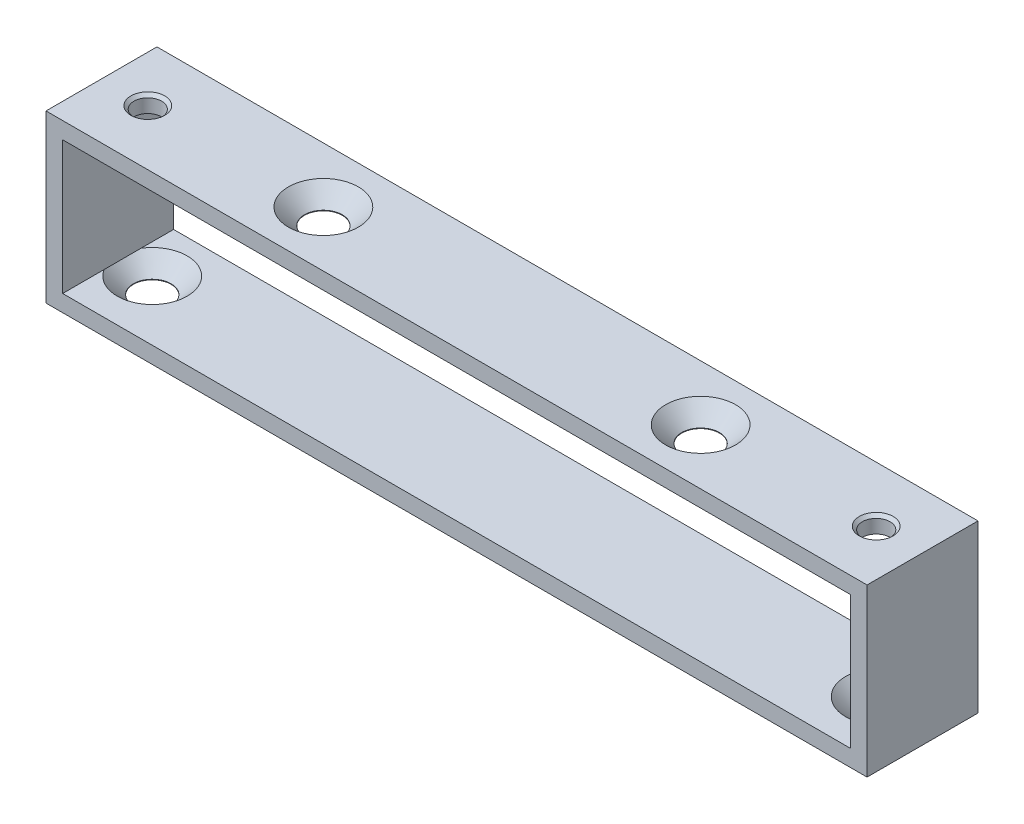
SolidWorks part; units mm, degrees
ref_plane "Ebene vorne" through (0, 0, 0) normal (0, 0, 1) x (1, 0, 0)
ref_plane "Ebene oben" through (0, 0, 0) normal (0, 1, 0) x (1, 0, 0)
ref_plane "Ebene rechts" through (0, 0, 0) normal (1, 0, 0) x (0, 0, -1)
sketch "Skizze1" plane through (0, 0, 0) normal (0, 0, 1) x (1, 0, 0)
  line L1 (-16.6079, 3.6552) -> (57.3921, 3.6552)
  line L2 (-16.6079, 3.6552) -> (-16.6079, -11.3448)
  line L3 (-16.6079, -11.3448) -> (57.3921, -11.3448)
  line L4 (57.3921, 3.6552) -> (57.3921, -11.3448)
  dimension "D1" = 15
  dimension "D2" = 74
extrude "Aufsatz-Linear austragen1" add sketch "Skizze1" along normal blind 10
sketch "Skizze2" plane through (0, 0, 10) normal (0, 0, 1) x (1, 0, 0)
  line L0 (-16.6079, 3.6552) -> (-16.6079, -11.3448) construction
  line L1 (-15.1079, 2.1552) -> (55.8921, 2.1552)
  line L2 (-15.1079, 2.1552) -> (-15.1079, -9.8448)
  line L3 (-15.1079, -9.8448) -> (55.8921, -9.8448)
  line L4 (55.8921, 2.1552) -> (55.8921, -9.8448)
  line L5 (57.3921, 3.6552) -> (-16.6079, 3.6552) construction
  dimension "D1" = 71
  dimension "D2" = 12
  dimension "D3" = 1.5
  dimension "D4" = 1.5
extrude "Schnitt-Linear austragen1" cut sketch "Skizze2" against normal up to next
sketch "Skizze3" plane through (0, 3.6552, 0) normal (0, 1, 0) x (1, 0, 0)
  line L0 (57.3921, -10) -> (-16.6079, -10) construction
  line L1 (57.3921, -10) -> (57.3921, 0) construction
  line L2 (-16.6079, -10) -> (-16.6079, 0) construction
  point P0 (-12.4329, -5)
  point P1 (53.2171, -5)
  dimension "D1" = 5
  dimension "D2" = 65.65
  dimension "D3" = 4.175
  dimension "D4" = 4.175
  dimension "D5" = 5
sketch "Skizze6" plane through (0, -9.8448, 0) normal (0, 1, 0) x (1, 0, 0)
  line L0 (-15.1079, -10) -> (55.8921, -10) construction
  line L1 (-16.6079, -10) -> (-16.6079, 0) construction
  line L2 (57.3921, -10) -> (57.3921, 0) construction
  line L4 (-16.6079, -10) -> (57.3921, -10) construction
  point P0 (-12.4329, -4.6)
  point P1 (53.2171, -4.6)
  dimension "D1" = 5.4
  dimension "D2" = 5.4
  dimension "D3" = 65.65
  dimension "D4" = 4.175
  dimension "D5" = 4.175
sketch "Skizze9" plane through (0, 3.6552, 0) normal (0, 1, 0) x (1, 0, 0)
  line L0 (57.3921, -10) -> (-16.6079, -10) construction
  line L1 (-16.6079, -10) -> (-16.6079, 0) construction
  line L2 (57.3921, -10) -> (57.3921, 0) construction
  point P0 (3.3921, -5)
  point P1 (37.3921, -5)
  dimension "D1" = 5
  dimension "D2" = 5
  dimension "D3" = 20
  dimension "D4" = 20
hole_wizard "Formsenkung für M3 Linsensenkschraube mit Schlitz2" positions "3D-Skizze3" profile "Skizze10" countersink size "M3" standard "ISO" end condition up to next
sketch3d "3D-Skizze3"
  point P0 (3.3921, 3.6552, 5)
  point P3 (37.3921, 3.6552, 5)
sketch "Skizze10" plane through (3.3921, 3.6552, 5) normal (1, 0, 0) x (0, 0, 1)
  line L0 (0, 0) -> (0, 1.5)
  line L1 (0, 1.5) -> (1.7, 1.5)
  line L2 (1.7, 1.5) -> (1.7, 1.45)
  line L3 (1.7, 1.45) -> (3.15, 0)
  line L5 (3.15, 0) -> (0, 0)
  line L6 (-1.7, 1.45) -> (-3.15, 0) construction
  line L11 (0, -6.35) -> (0, 107.95) construction
  dimension "Bohrerdurchmesser" = 3.4
  dimension "Bohrungstiefe" = 1.5
  dimension "Senkdurchmesser (Oben)" = 6.3
  dimension "Senkwinkel (Oben)" = 90
hole_wizard "M3 Gewindebohrung1" positions "3D-Skizze5" profile "Skizze12" tap size "M3" standard "ISO" end condition up to next
sketch3d "3D-Skizze5"
  point P0 (53.2171, 3.6552, 5)
  point P3 (-12.4329, 3.6552, 5)
sketch "Skizze12" plane through (53.2171, 3.6552, 5) normal (1, 0, 0) x (0, 0, 1)
  line L0 (0, 0) -> (0, 1.5)
  line L1 (0, 1.5) -> (1.25, 1.5)
  line L2 (1.25, 1.5) -> (1.25, 0.275)
  line L3 (1.25, 0.275) -> (1.525, 0)
  line L5 (1.525, 0) -> (0, 0)
  line L6 (-1.25, 0.275) -> (-1.525, 0) construction
  line L11 (0, -6.35) -> (0, 107.95) construction
  dimension "Bohrerdurchmesser" = 2.5
  dimension "Bohrungstiefe" = 1.5
  dimension "Senkdurchmesser (Oben)" = 3.05
  dimension "Senkwinkel (Oben)" = 90
cosmetic thread "Bohrungsgewinde1" parameters "D2"=3
cosmetic thread "Bohrungsgewinde2" parameters "D2"=3
hole_wizard "Formsenkung für M3 Linsensenkschraube mit Schlitz4" positions "3D-Skizze6" profile "Skizze13" countersink size "M3" standard "ISO" end condition up to next
sketch3d "3D-Skizze6"
  point P0 (-12.4329, -9.8448, 4.6)
  point P3 (53.2171, -9.8448, 4.6)
sketch "Skizze13" plane through (-12.4329, -9.8448, 4.6) normal (1, 0, 0) x (0, 0, 1)
  line L0 (0, 0) -> (0, 1.5)
  line L1 (0, 1.5) -> (1.7, 1.5)
  line L2 (1.7, 1.5) -> (1.7, 1.45)
  line L3 (1.7, 1.45) -> (3.15, 0)
  line L5 (3.15, 0) -> (0, 0)
  line L6 (-1.7, 1.45) -> (-3.15, 0) construction
  line L11 (0, -6.35) -> (0, 107.95) construction
  dimension "Bohrerdurchmesser" = 3.4
  dimension "Bohrungstiefe" = 1.5
  dimension "Senkdurchmesser (Oben)" = 6.3
  dimension "Senkwinkel (Oben)" = 90
